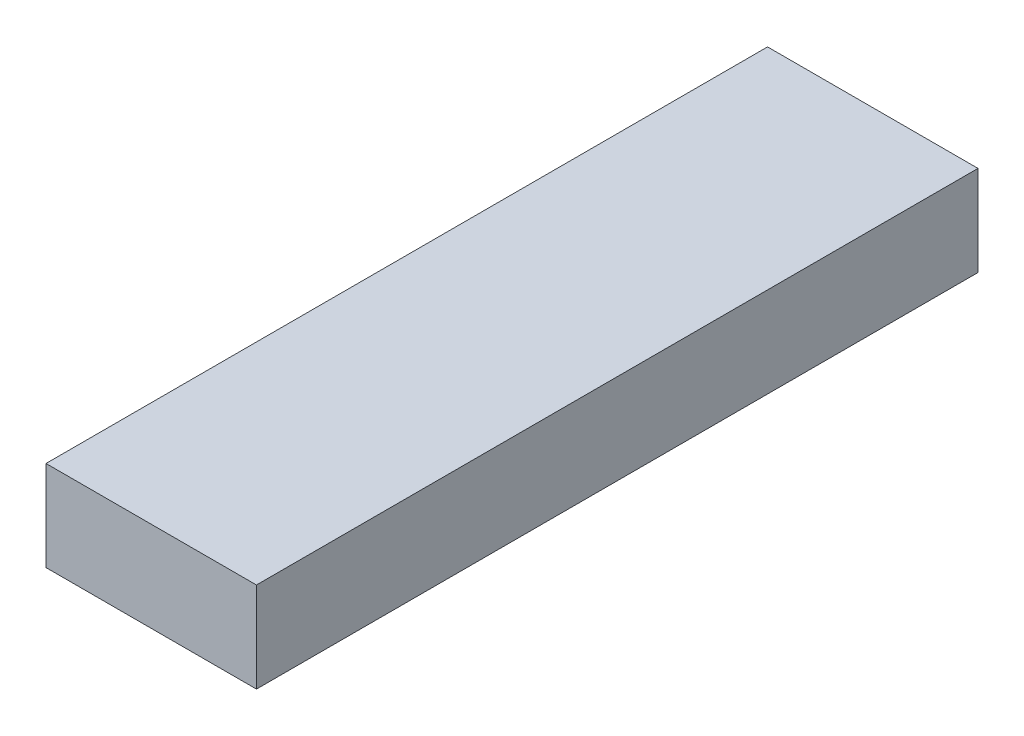
SolidWorks part; units mm, degrees
material "Pine"
ref_plane "Front Plane" through (0, 0, 0) normal (0, 0, 1) x (1, 0, 0)
ref_plane "Top Plane" through (0, 0, 0) normal (0, 1, 0) x (1, 0, 0)
ref_plane "Right Plane" through (0, 0, 0) normal (1, 0, 0) x (0, 0, -1)
sketch "Sketch1" plane through (0, 0, 0) normal (0, 0, 1) x (1, 0, 0)
  line L1 (44.45, -19.05) -> (-44.45, -19.05)
  line L2 (44.45, -19.05) -> (44.45, 19.05)
  line L3 (44.45, 19.05) -> (-44.45, 19.05)
  line L4 (-44.45, -19.05) -> (-44.45, 19.05)
  line L5 (44.45, -19.05) -> (-44.45, 19.05) construction
  line L6 (44.45, 19.05) -> (-44.45, -19.05) construction
  point P0 (0, 0)
  dimension "D1" = 88.9
  dimension "D2" = 38.1
extrude "Boss-Extrude1" add sketch "Sketch1" along normal blind 304.8
